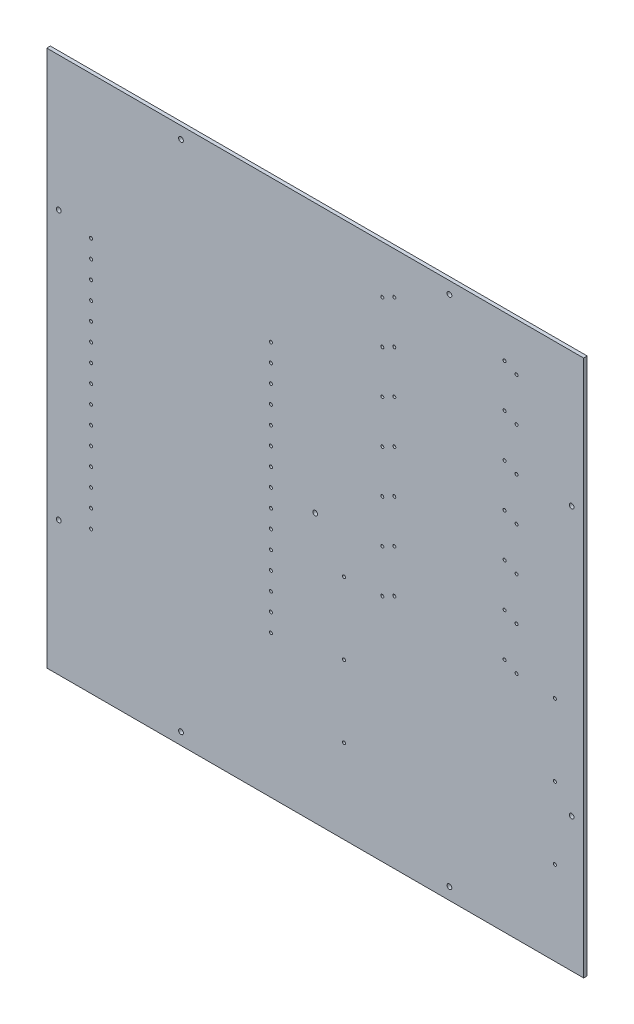
SolidWorks part; units mm, degrees
material "6061-T6 (SS)"
ref_plane "Piano frontale" through (0, 0, 0) normal (0, 0, 1) x (1, 0, 0)
ref_plane "Piano superiore" through (0, 0, 0) normal (0, 1, 0) x (1, 0, 0)
ref_plane "Piano destro" through (0, 0, 0) normal (1, 0, 0) x (0, 0, -1)
sketch "Schizzo1" plane through (0, 0, 0) normal (0, 0, 1) x (1, 0, 0)
  line L0 (10, 448) -> (10, -28.2593) construction
  line L1 (0, 0) -> (448, 0)
  line L2 (0, 0) -> (0, 448)
  line L3 (0, 448) -> (448, 448)
  line L4 (448, 0) -> (448, 448)
  line L5 (0, 224) -> (448, 224) construction
  line L6 (224, 448) -> (224, 0) construction
  line L7 (438, 448) -> (438, -28.2593) construction
  line L8 (0, 438) -> (525.0128, 438) construction
  line L9 (0, 10) -> (525.0128, 10) construction
  line L10 (0, 448) -> (0, 224) construction
  line L11 (0, 448) -> (0, 224) construction
  line L15 (0, 336) -> (224, 336) construction
  line L25 (112, 448) -> (112, 224) construction
  line L38 (36.9588, 287.1268) -> (36.9588, 448) construction
  line L39 (290, 454.3859) -> (290, -79.8136) construction
  line L40 (382, 454.3859) -> (382, -79.8136) construction
  line L41 (280, 457.4164) -> (280, -41.798) construction
  line L42 (392, 457.4164) -> (392, -41.798) construction
  line L43 (204.2813, 100) -> (482.2381, 100) construction
  line L44 (183.4892, 70) -> (499.6284, 70) construction
  line L45 (248, -38.4576) -> (248, 170.1585) construction
  line L46 (183.4892, 130) -> (499.6284, 130) construction
  line L47 (424, -38.4576) -> (424, 170.1585) construction
  line L58 (336, 27.7675) -> (336, 161.4481) construction
  line L65 (224, 224) -> (448, 224) construction
  circle A0 centre (10, 336) radius 2
  circle A1 centre (336, 438) radius 2
  circle A2 centre (438, 336) radius 2
  circle A3 centre (438, 112) radius 2
  circle A4 centre (336, 10) radius 2
  circle A5 centre (112, 10) radius 2
  circle A6 centre (10, 112) radius 2
  circle A7 centre (36.9588, 224) radius 1.25
  circle A8 centre (112, 438) radius 2
  circle A9 centre (36.9588, 239) radius 1.25
  circle A10 centre (36.9588, 254) radius 1.25
  circle A11 centre (36.9588, 269) radius 1.25
  circle A12 centre (36.9588, 284) radius 1.25
  circle A13 centre (36.9588, 299) radius 1.25
  circle A14 centre (36.9588, 314) radius 1.25
  circle A15 centre (36.9588, 329) radius 1.25
  circle A16 centre (248, 70) radius 1.25
  circle A17 centre (248, 130) radius 1.25
  circle A18 centre (424, 130) radius 1.25
  circle A19 centre (424, 70) radius 1.25
  circle A20 centre (290, 413) radius 1.25
  circle A21 centre (280, 408) radius 1.25
  circle A22 centre (392, 408) radius 1.25
  circle A23 centre (382, 413) radius 1.25
  circle A24 centre (290, 377) radius 1.25
  circle A25 centre (280, 372) radius 1.25
  circle A26 centre (392, 372) radius 1.25
  circle A27 centre (382, 377) radius 1.25
  circle A28 centre (290, 341) radius 1.25
  circle A29 centre (280, 336) radius 1.25
  circle A30 centre (392, 336) radius 1.25
  circle A31 centre (382, 341) radius 1.25
  circle A32 centre (290, 305) radius 1.25
  circle A33 centre (280, 300) radius 1.25
  circle A34 centre (392, 300) radius 1.25
  circle A35 centre (382, 305) radius 1.25
  circle A36 centre (290, 269) radius 1.25
  circle A37 centre (280, 264) radius 1.25
  circle A38 centre (392, 264) radius 1.25
  circle A39 centre (382, 269) radius 1.25
  circle A40 centre (290, 233) radius 1.25
  circle A41 centre (280, 228) radius 1.25
  circle A42 centre (392, 228) radius 1.25
  circle A43 centre (382, 233) radius 1.25
  circle A44 centre (290, 197) radius 1.25
  circle A45 centre (280, 192) radius 1.25
  circle A46 centre (392, 192) radius 1.25
  circle A47 centre (382, 197) radius 1.25
  circle A48 centre (36.9588, 119) radius 1.25
  circle A49 centre (36.9588, 134) radius 1.25
  circle A50 centre (36.9588, 149) radius 1.25
  circle A51 centre (36.9588, 164) radius 1.25
  circle A52 centre (36.9588, 179) radius 1.25
  circle A53 centre (36.9588, 194) radius 1.25
  circle A54 centre (36.9588, 209) radius 1.25
  circle A55 centre (187.0412, 209) radius 1.25
  circle A56 centre (187.0412, 194) radius 1.25
  circle A57 centre (187.0412, 179) radius 1.25
  circle A58 centre (187.0412, 164) radius 1.25
  circle A59 centre (187.0412, 149) radius 1.25
  circle A60 centre (187.0412, 134) radius 1.25
  circle A61 centre (187.0412, 119) radius 1.25
  circle A62 centre (187.0412, 329) radius 1.25
  circle A63 centre (187.0412, 314) radius 1.25
  circle A64 centre (187.0412, 299) radius 1.25
  circle A65 centre (187.0412, 284) radius 1.25
  circle A66 centre (187.0412, 269) radius 1.25
  circle A67 centre (187.0412, 254) radius 1.25
  circle A68 centre (187.0412, 239) radius 1.25
  circle A69 centre (187.0412, 224) radius 1.25
  circle A70 centre (224, 224) radius 2
  circle A71 centre (424, 190) radius 1.25
  circle A72 centre (248, 190) radius 1.25
  point P33 (36.9588, 224)
  point P49 (112, 438)
  point P82 (253.9707, 256)
  point P89 (253.9707, 224)
  point P96 (253.9707, 192)
  point P103 (253.9707, 384)
  point P110 (253.9707, 352)
  point P117 (253.9707, 320)
  point P141 (253.9707, 288)
  point P148 (253.9707, 160)
  point P155 (253.9707, 128)
  point P162 (253.9707, 96)
  point P169 (253.9707, 64)
  point P179 (280.1758, 232.4048)
  point P193 (280.1085, 282.4047)
  point P207 (280.0413, 332.4047)
  dimension "D5" = 30
  dimension "D14" = 100
  dimension "D18" = 7
  dimension "D16" = 2.5
  dimension "D17" = 2.5
  dimension "D9" = 4
  dimension "D10" = 2.5
  dimension "D20" = 4
  dimension "D1" = 448
  dimension "D2" = 448
  dimension "D3" = 10
  dimension "D4" = 10
  dimension "D6" = 25
  dimension "D7" = 112
  dimension "D8" = 112
  dimension "D11" = 46
  dimension "D12" = 56
  dimension "D13" = 30
  dimension "D15" = 88
  dimension "D19" = 8
extrude "Estrusione-Estrusione1" add sketch "Schizzo1" against normal blind 3
